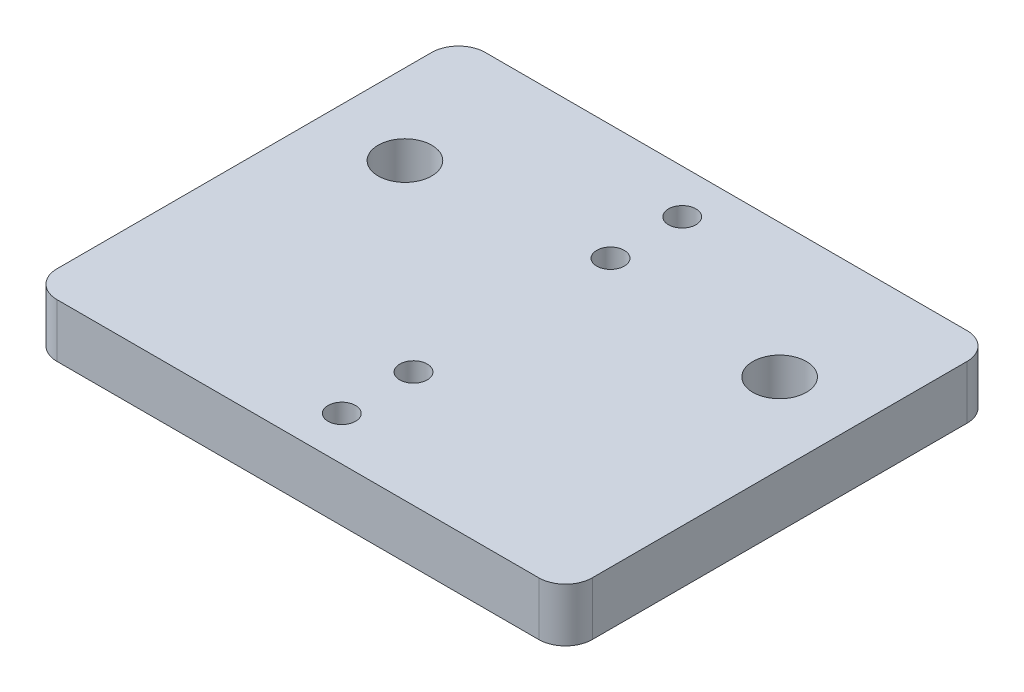
SolidWorks part; units mm, degrees
ref_plane "Front Plane" through (0, 0, 0) normal (0, 0, 1) x (1, 0, 0)
ref_plane "Top Plane" through (0, 0, 0) normal (0, 1, 0) x (1, 0, 0)
ref_plane "Right Plane" through (0, 0, 0) normal (1, 0, 0) x (0, 0, -1)
sketch "Sketch1" plane through (0, 0, 0) normal (0, 1, 0) x (1, 0, 0)
  line L0 (0, 50.8) -> (0, -50.8) construction
  line L1 (-63.5, -6.35) -> (63.5, -6.35) construction
  line L2 (-63.5, -6.35) -> (-63.5, 6.35) construction
  line L3 (-63.5, 6.35) -> (63.5, 6.35) construction
  line L4 (63.5, -6.35) -> (63.5, 6.35) construction
  line L5 (-63.5, -6.35) -> (63.5, 6.35) construction
  line L6 (-63.5, 6.35) -> (63.5, -6.35) construction
  line L7 (-63.5, -50.8) -> (63.5, -50.8)
  line L8 (-63.5, -50.8) -> (-63.5, 50.8)
  line L9 (-63.5, 50.8) -> (63.5, 50.8)
  line L10 (63.5, -50.8) -> (63.5, 50.8)
  line L11 (-63.5, -50.8) -> (63.5, 50.8) construction
  line L12 (-63.5, 50.8) -> (63.5, -50.8) construction
  line L13 (-63.5, 0) -> (63.5, 0) construction
  circle A0 centre (0, 23.368) radius 3.2639
  circle A1 centre (0, 40.386) radius 3.2639
  circle A2 centre (0, -23.368) radius 3.2639
  circle A3 centre (0, -40.386) radius 3.2639
  circle A4 centre (-44.45, 19.05) radius 6.35
  circle A5 centre (44.45, 19.05) radius 6.35
  point P0 (0, 0)
  point P6 (0, 0)
  dimension "D6" = 6.5278
  dimension "D9" = 12.7
  dimension "D1" = 12.7
  dimension "D2" = 127
  dimension "D3" = 44.45
  dimension "D4" = 17.018
  dimension "D5" = 17.018
  dimension "D7" = 127
  dimension "D8" = 88.9
  dimension "D10" = 19.05
  dimension "D11" = 31.75
extrude "Boss-Extrude1" add sketch "Sketch1" along normal mid plane 12.7
fillet "Fillet1" radius 6.35 4 edges at (-63.5, 0, -50.8) (63.5, 0, -50.8) (63.5, 0, 50.8) (-63.5, 0, 50.8)
